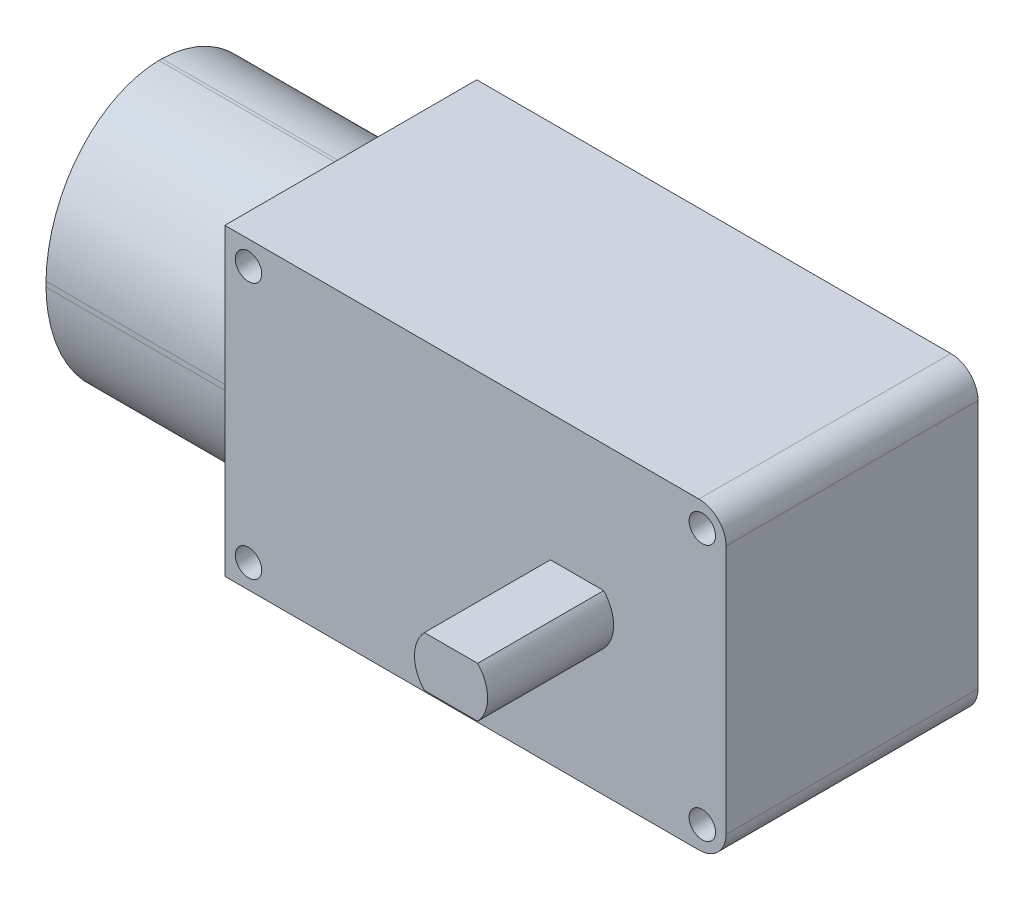
SolidWorks part; units mm, degrees
ref_plane "Front Plane" through (0, 0, 0) normal (0, 0, 1) x (1, 0, 0)
ref_plane "Top Plane" through (0, 0, 0) normal (0, 1, 0) x (1, 0, 0)
ref_plane "Right Plane" through (0, 0, 0) normal (1, 0, 0) x (0, 0, -1)
sketch "Sketch1" plane through (0, 0, 0) normal (0, 0, 1) x (1, 0, 0)
  line L1 (-18.5, -11.22) -> (18.5, -11.22)
  line L2 (-18.5, -11.22) -> (-18.5, 11.22)
  line L3 (-18.5, 11.22) -> (18.5, 11.22)
  line L4 (18.5, -11.22) -> (18.5, 11.22)
  line L5 (-18.5, -11.22) -> (18.5, 11.22) construction
  line L6 (-18.5, 11.22) -> (18.5, -11.22) construction
  point P0 (0, 0)
  dimension "D1" = 37
  dimension "D2" = 22.44
extrude "Boss-Extrude1" add sketch "Sketch1" along normal blind 18.6 contours L2 L3 L4 L1
fillet "Fillet1" radius 2 2 edges at (18.5, -11.22, 9.3) (18.5, 11.22, 9.3)
sketch "Sketch2" plane through (-18.5, 0, 0) normal (-1, 0, 0) x (0, 0, 1)
  line L0 (0, -11.22) -> (0, 11.22) construction
  line L1 (0.8, 10.19) -> (17.8, 10.19)
  line L2 (0.8, 10.19) -> (0.8, -10.19)
  line L3 (0.8, -10.19) -> (17.8, -10.19)
  line L4 (17.8, 10.19) -> (17.8, -10.19)
  line L7 (18.6, 11.22) -> (0, 11.22) construction
  line L8 (18.6, -11.22) -> (0, -11.22) construction
  dimension "D1" = 17
  dimension "D2" = 0.8
  dimension "D3" = 20.38
  dimension "D4" = 1.03
  dimension "D5" = 1.03
extrude "Boss-Extrude2" add sketch "Sketch2" along normal blind 14
sketch "Sketch3" plane through (0, 0, 18.6) normal (0, 0, 1) x (1, 0, 0)
  line L0 (18.5, -9.22) -> (18.5, 9.22) construction
  line L1 (-18.5, 11.22) -> (16.5, 11.22) construction
  line L2 (7.5, -1.85) -> (7.5, 1.85)
  line L3 (6.3094, 1.85) -> (8.6906, 1.85)
  line L5 (6.3094, 1.85) -> (5.5334, 1.85)
  line L6 (5.5334, 1.85) -> (9.4666, 1.85)
  line L7 (5.5334, -1.85) -> (9.4666, -1.85)
  arc A0 (5.5334, 1.85) -> (5.5334, -1.85) centre (7.5, 0) ccw
  arc A1 (6.3094, 1.85) -> (6.3094, -1.85) centre (7.5, 0) ccw
  circle A2 centre (7.5, 0) radius 2.7 construction
  circle A3 centre (7.5, 0) radius 2.2 construction
  arc A4 (9.4666, -1.85) -> (9.4666, 1.85) centre (7.5, 0) ccw
  arc A5 (8.6906, -1.85) -> (8.6906, 1.85) centre (7.5, 0) ccw
  point P11 (7.5, 0)
  point P14 (7.5, 1.85)
  point P17 (7.5, -1.85)
  dimension "D1" = 5.4
  dimension "D2" = 11
  dimension "D3" = 11.22
  dimension "D4" = 0.5
  dimension "D5" = 3.7
extrude "Boss-Extrude3" add sketch "Sketch3" along normal blind 9.3 and the other way blind 26.7 contours L6 A4 L7 A0
sketch "Sketch4" plane through (-32.5, 0, 0) normal (-1, 0, 0) x (0, 0, 1)
  line L0 (17.8, 10.19) -> (0.8, 10.19) construction
  line L1 (0.8, 0.1354) -> (0.8, 10.19)
  line L2 (0.8, 10.19) -> (17.8, 10.19)
  line L3 (17.8, 10.19) -> (17.8, -10.19)
  line L4 (17.8, -10.19) -> (0.8, -10.19)
  line L5 (0.8, -10.19) -> (0.8, 0.1354)
  ellipse E0 centre (9.3, 0) end of major axis (9.4624, 10.19) minor radius 8.5011
  line M1 (0.8, 10.19) -> (0.8, -10.19)
  line M2 (0.8, -10.19) -> (17.8, -10.19)
  line M3 (17.8, -10.19) -> (17.8, 10.19)
  line M4 (17.8, 10.19) -> (0.8, 10.19)
extrude "Cut-Extrude1" cut sketch "Sketch4" against normal up to surface (14 mm away) contours E0 M4 M1 | E0 M3 M4 | E0 M2 M3 | E0 L5 M2 up to face at (-18.5, 0, 9.3)
sketch "Sketch5" plane through (0, 0, 0) normal (0, 0, -1) x (-1, 0, 0)
  line L0 (18.5, 11.22) -> (-16.5, 11.22) construction
  line L1 (18.5, -11.22) -> (-16.5, -11.22) construction
  line L2 (18.5, 0.1354) -> (18.5, 10.19) construction
  line L3 (-18.5, -9.22) -> (-18.5, 9.22) construction
  line L4 (18.5, -11.22) -> (18.5, 11.22) construction
  circle A0 centre (-16.75, 9.47) radius 0.975
  circle A1 centre (-16.75, -9.47) radius 0.975
  circle A2 centre (16.75, -9.47) radius 0.975
  circle A3 centre (16.75, 9.47) radius 0.975
  dimension "D8" = 1.95
  dimension "D1" = 1.75
  dimension "D2" = 22.44
  dimension "D3" = 1.75
  dimension "D4" = 37
  dimension "D5" = 1.75
  dimension "D7" = 1.75
extrude "Cut-Extrude2" cut sketch "Sketch5" against normal through all
